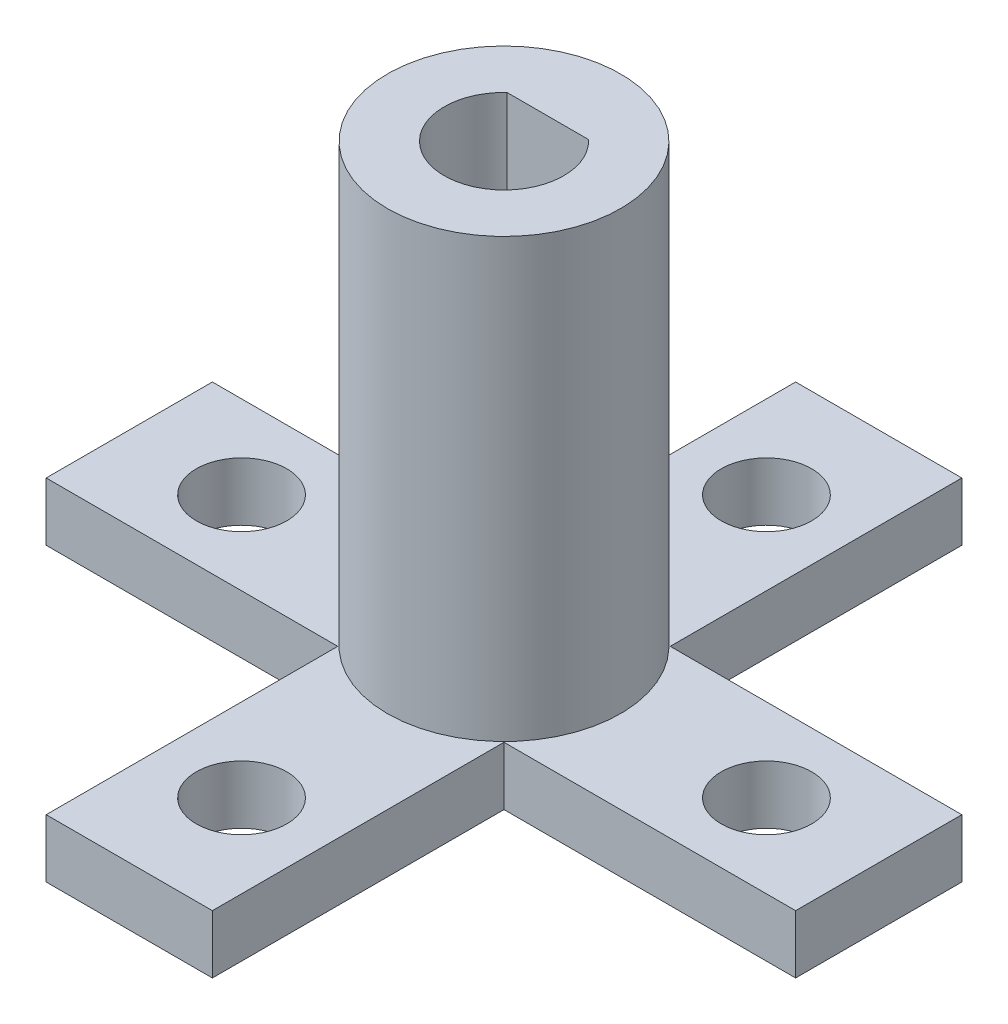
SolidWorks part; units mm, degrees
ref_plane "前视基准面" through (0, 0, 0) normal (0, 0, 1) x (1, 0, 0)
ref_plane "上视基准面" through (0, 0, 0) normal (0, 1, 0) x (1, 0, 0)
ref_plane "右视基准面" through (0, 0, 0) normal (1, 0, 0) x (0, 0, -1)
other "Configuration Table"
sketch "草图1" plane through (0, 0, 0) normal (0, 1, 0) x (1, 0, 0)
  line L0 (0, 0) -> (0, 9)
  line L1 (-12.85, -2.85) -> (12.85, -2.85)
  line L2 (-12.85, -2.85) -> (-12.85, 2.85)
  line L3 (-12.85, 2.85) -> (12.85, 2.85)
  line L4 (12.85, -2.85) -> (12.85, 2.85)
  line L5 (-12.85, -2.85) -> (12.85, 2.85) construction
  line L6 (-12.85, 2.85) -> (12.85, -2.85) construction
  line L7 (-2.85, 12.85) -> (2.85, 12.85)
  line L8 (-2.85, 12.85) -> (-2.85, -12.85)
  line L9 (-2.85, -12.85) -> (2.85, -12.85)
  line L10 (2.85, 12.85) -> (2.85, -12.85)
  line L11 (-2.85, 12.85) -> (2.85, -12.85) construction
  line L12 (-2.85, -12.85) -> (2.85, 12.85) construction
  circle A0 centre (0, 9) radius 1.55
  circle A1 centre (9, 0) radius 1.55
  circle A2 centre (0, -9) radius 1.55
  circle A3 centre (-9, 0) radius 1.55
  point P0 (0, 0)
  point P6 (0, 0)
  dimension "D6" = 3.1
  dimension "D1" = 25.7
  dimension "D2" = 5.7
  dimension "D3" = 25.7
  dimension "D4" = 5.7
  dimension "D5" = 9
  dimension "D7" = 4
extrude "凸台-拉伸1" add sketch "草图1" along normal blind 2
sketch "草图2" plane through (0, 2, 0) normal (0, 1, 0) x (1, 0, 0)
  circle A0 centre (0, 0) radius 4
  dimension "D1" = 8
extrude "凸台-拉伸2" add sketch "草图2" along normal blind 15
sketch "草图3" plane through (0, 17, 0) normal (0, 1, 0) x (1, 0, 0)
  line L0 (0, 0) -> (0, 1.5)
  line L1 (-1000, 1.5) -> (49000, 1.5)
  circle A0 centre (0, 0) radius 2.05
  dimension "D1" = 4.1
  dimension "D2" = 1.5
extrude "切除-拉伸1" cut sketch "草图3" against normal through all
sketch "草图4" plane through (0, 0, -1.5) normal (0, 0, 1) x (1, 0, 0)
  line L0 (0, 17) -> (0, 13)
  line L1 (4, 17) -> (-4, 17) construction
  circle A0 centre (0, 13) radius 1.5
  dimension "D2" = 3
  dimension "D1" = 4
extrude "切除-拉伸2" cut sketch "草图4" against normal through all
sketch "草图5" plane through (0, 0, -1.5) normal (0, 0, -1) x (-1, 0, 0)
  circle A0 centre (0, 13) radius 1.5
extrude "切除-拉伸3" cut sketch "草图5" against normal blind 1
